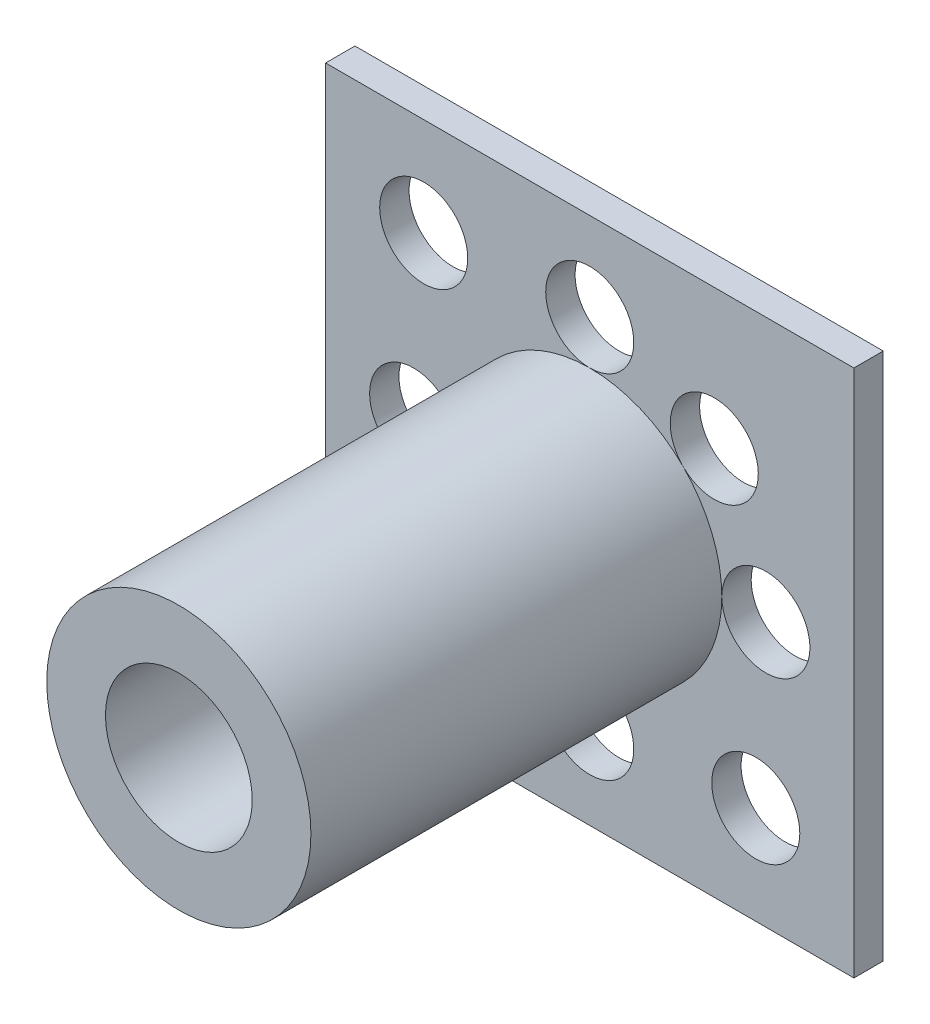
SolidWorks part; units mm, degrees
ref_plane "Front Plane" through (0, 0, 0) normal (0, 0, 1) x (1, 0, 0)
ref_plane "Top Plane" through (0, 0, 0) normal (0, 1, 0) x (1, 0, 0)
ref_plane "Right Plane" through (0, 0, 0) normal (1, 0, 0) x (0, 0, -1)
sketch "Sketch1" plane through (0, 0, 0) normal (0, 0, 1) x (1, 0, 0)
  circle A0 centre (0, 0) radius 4.5
  circle A2 centre (0, 0) radius 2.5
  dimension "D1" = 9
  dimension "D2" = 2
extrude "Boss-Extrude1" add sketch "Sketch1" along normal blind 15
sketch "Sketch2" plane through (0, 0, 0) normal (0, 0, 1) x (1, 0, 0)
  line L1 (9, -9) -> (-9, -9)
  line L2 (9, -9) -> (9, 9)
  line L3 (9, 9) -> (-9, 9)
  line L4 (-9, -9) -> (-9, 9)
  line L5 (9, -9) -> (-9, 9) construction
  line L6 (9, 9) -> (-9, -9) construction
  point P1 (0, 0)
  dimension "D1" = 18
extrude "Boss-Extrude2" add sketch "Sketch2" along normal blind 1
sketch "Sketch3" plane through (0, 0, 0) normal (0, 0, -1) x (-1, 0, 0)
  line L0 (9, 9) -> (-9, -9) construction
  line L1 (-9, 9) -> (9, -9) construction
  circle A0 centre (5.6569, 5.6569) radius 1.5
  circle A1 centre (-5.6569, -5.6569) radius 1.5
  circle A2 centre (-4.2426, 4.2426) radius 1.5
  circle A3 centre (4.2426, -4.2426) radius 1.5
  circle A4 centre (0, 0) radius 6 construction
  circle A5 centre (0, 6) radius 1.5
  circle A6 centre (0, 0) radius 6 construction
  circle A7 centre (6, 0) radius 1.5
  circle A8 centre (0, 0) radius 6 construction
  circle A9 centre (0, -6) radius 1.5
  circle A10 centre (0, 0) radius 6 construction
  circle A11 centre (-6, 0) radius 1.5
  circle A16 centre (0, 0) radius 2.5
  circle A17 centre (0, 0) radius 2.5 construction
  point P32 (0, 0)
  point P39 (0, 0)
  dimension "D3" = 3
  dimension "D5" = 12
  dimension "D1" = 16
  dimension "D4" = 12
  dimension "D7" = 4
extrude "Cut-Extrude1" cut sketch "Sketch3" against normal blind 2 contours A1 | A9 | A11 | A3 | A0 | A5 | A2
